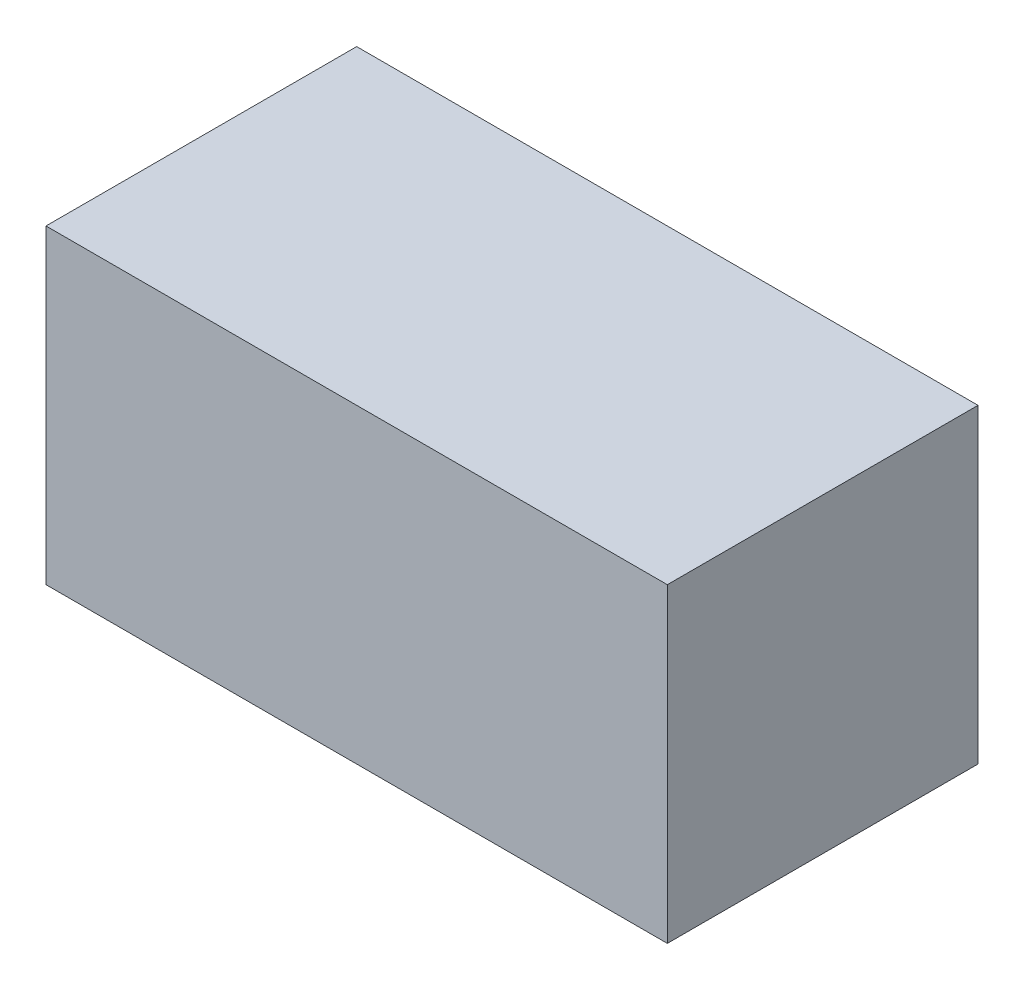
SolidWorks part; units mm, degrees
ref_plane "Front Plane" through (0, 0, 0) normal (0, 0, 1) x (1, 0, 0)
ref_plane "Top Plane" through (0, 0, 0) normal (0, 1, 0) x (1, 0, 0)
ref_plane "Right Plane" through (0, 0, 0) normal (1, 0, 0) x (0, 0, -1)
sketch "Sketch1" plane through (0, 0, 0) normal (0, 0, 1) x (1, 0, 0)
  line L1 (0, 0) -> (70, 0)
  line L2 (0, 0) -> (0, 35)
  line L3 (0, 35) -> (70, 35)
  line L4 (70, 0) -> (70, 35)
  dimension "D1" = 70
  dimension "D2" = 35
extrude "Boss-Extrude1" add sketch "Sketch1" along normal blind 35
